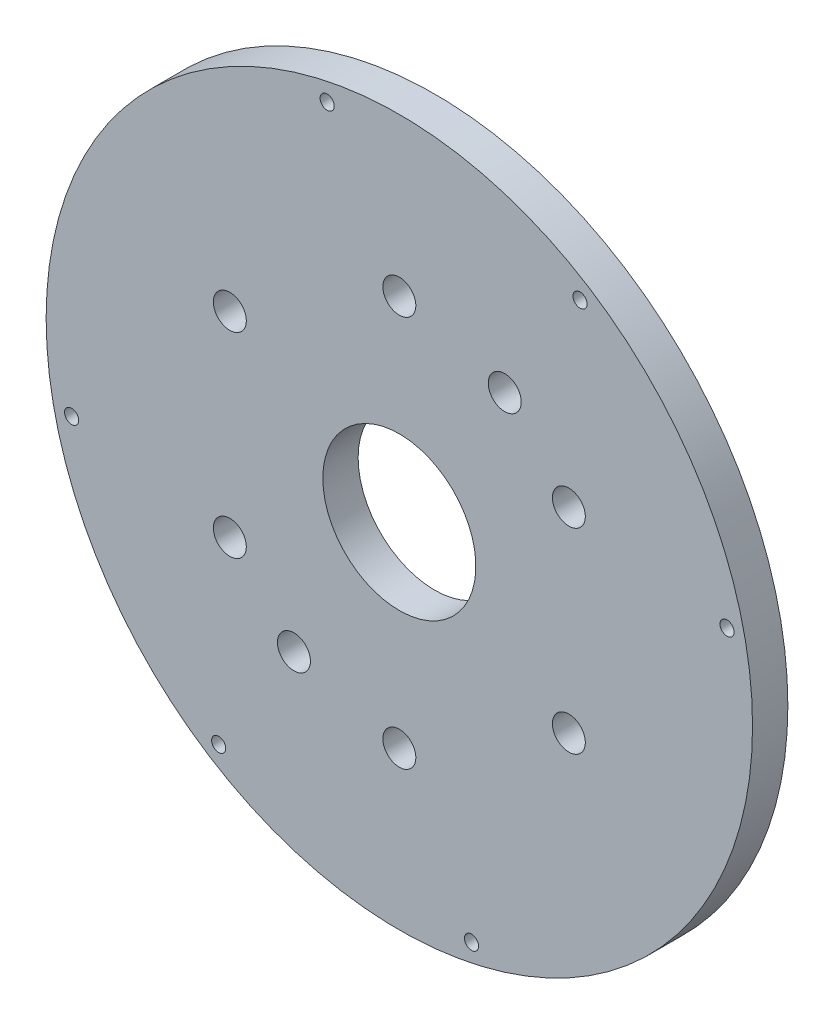
SolidWorks part; units mm, degrees
ref_plane "Front Plane" through (0, 0, 0) normal (0, 0, 1) x (1, 0, 0)
ref_plane "Top Plane" through (0, 0, 0) normal (0, 1, 0) x (1, 0, 0)
ref_plane "Right Plane" through (0, 0, 0) normal (1, 0, 0) x (0, 0, -1)
sketch "Sketch1" plane through (0, 0, 0) normal (0, 0, 1) x (1, 0, 0)
  circle A0 centre (0, 0) radius 60
  dimension "D1" = 120
extrude "Boss-Extrude1" add sketch "Sketch1" against normal blind 6
sketch "Sketch2" plane through (0, 0, -6) normal (0, 0, -1) x (-1, 0, 0)
  circle A0 centre (0, 0) radius 13
  dimension "D1" = 26
extrude "Cut-Extrude1" cut sketch "Sketch2" against normal through all both and the other way through all
sketch "Sketch4" plane through (0, 0, -6) normal (0, 0, -1) x (-1, 0, 0)
  line L0 (0, 0) -> (0, -72.0278) construction
  circle A0 centre (0, 0) radius 33.25
  point P3 (0, -33.25)
  point P8 (-28.7953, -16.625)
  point P9 (-28.7953, 16.625)
  point P10 (0, 33.25)
  point P11 (28.7953, 16.625)
  point P12 (28.7953, -16.625)
  point P13 (0, 0)
  dimension "D1" = 66.5
  dimension "D2" = 6
hole_wizard "Ø4.0mm Dowel Hole1" positions "Sketch4" profile "Sketch5" hole size "Ø4.0" standard "ANSI Metric" end condition through all
sketch "Sketch5" plane through (0, 0, -6) normal (1, 0, 0) x (0, 1, 0)
  line L0 (0, 0) -> (0, 6)
  line L1 (0, 6) -> (2.8, 6)
  line L2 (2.8, 6) -> (2.8, 0)
  line L5 (2.8, 0) -> (0, 0)
  line L11 (0, -6.35) -> (0, 107.95) construction
  dimension "Thru Hole Dia." = 5.6
  dimension "Thru Hole Depth" = 6
sketch "Sketch7" plane through (0, 0, 0) normal (0, 0, 1) x (1, 0, 0)
  circle A0 centre (0, 0) radius 33.25
  point P0 (17.9032, 28.0185)
  point P1 (-17.9032, -28.0185)
hole_wizard "Ø1.0mm Dowel Hole1" positions "Sketch7" profile "Sketch8" hole size "Ø1.0" standard "ANSI Metric" end condition through all
sketch "Sketch8" plane through (17.9032, 28.0185, 0) normal (1, 0, 0) x (0, -1, 0)
  line L0 (0, 0) -> (0, 6)
  line L1 (0, 6) -> (2.8, 6)
  line L2 (2.8, 6) -> (2.8, 0)
  line L5 (2.8, 0) -> (0, 0)
  line L11 (0, -6.35) -> (0, 107.95) construction
  dimension "Thru Hole Dia." = 5.6
  dimension "Thru Hole Depth" = 6
sketch "Sketch9" plane through (0, 0, -6) normal (0, 0, -1) x (-1, 0, 0)
  line L0 (0, 0) -> (0, 60) construction
  line L1 (0, 0) -> (-32.7298, 51.2222) construction
  line L2 (0, 0) -> (-55.6655, 12.2617) construction
  circle A0 centre (0, 0) radius 57 construction
  circle A1 centre (0, 0) radius 60 construction
  circle A3 centre (-17.9032, 28.0185) radius 2.8 construction
  circle A4 centre (-17.9032, 28.0185) radius 2.8 construction
  point P12 (-30.6912, 48.0318)
  point P16 (12.2617, 55.6655)
  point P17 (48.0318, 30.6912)
  point P18 (55.6655, -12.2617)
  point P19 (30.6912, -48.0318)
  point P20 (-12.2617, -55.6655)
  point P21 (-48.0318, -30.6912)
  point P22 (-55.6655, 12.2617)
  point P23 (0, 0)
  dimension "D1" = 3
  dimension "D2" = 8
  dimension "D3" = 77.578
hole_wizard "CBORE for M2 SHCS3" positions "Sketch10" profile "Sketch11" counterbore size "M2" standard "ANSI Metric"
sketch "Sketch10" plane through (0, 0, -6) normal (0, 0, -1) x (-1, 0, 0)
  point P0 (-55.6655, 12.2617)
  point P3 (-30.6912, 48.0318)
  point P6 (12.2617, 55.6655)
  point P9 (48.0318, 30.6912)
  point P12 (55.6655, -12.2617)
  point P15 (30.6912, -48.0318)
  point P18 (-12.2617, -55.6655)
  point P21 (-48.0318, -30.6912)
sketch "Sketch11" plane through (55.6655, 12.2617, -6) normal (1, 0, 0) x (0, 1, 0)
  line L0 (0, 0) -> (0, 6)
  line L1 (0, 6) -> (1.2, 6)
  line L3 (1.2, 6) -> (1.2, 2)
  line L4 (1.2, 2) -> (2.2, 2)
  line L5 (2.2, 2) -> (2.2, 0)
  line L7 (2.2, 0) -> (0, 0)
  line L11 (0, -6.35) -> (0, 107.95) construction
  dimension "Thru Hole Dia." = 2.4
  dimension "Thru Hole Depth" = 6
  dimension "C'Bore Dia." = 4.4
  dimension "C'Bore Depth" = 2
